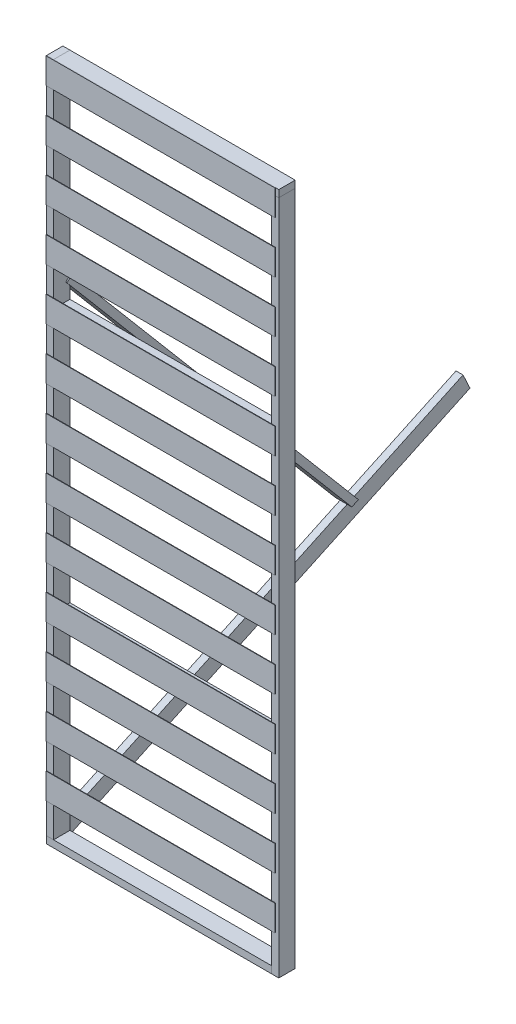
SolidWorks part; units mm, degrees
ref_plane "Front Plane" through (0, 0, 0) normal (0, 0, 1) x (1, 0, 0)
ref_plane "Top Plane" through (0, 0, 0) normal (0, 1, 0) x (1, 0, 0)
ref_plane "Right Plane" through (0, 0, 0) normal (1, 0, 0) x (0, 0, -1)
sketch "Sketch2" plane through (0, 0, 0) normal (0, 0, 1) x (1, 0, 0)
  line L0 (-609.6, 660.4) -> (609.6, 660.4)
  line L1 (-609.6, 1828.8) -> (609.6, 1828.8)
  line L2 (-609.6, 1828.8) -> (-609.6, -1828.8)
  line L3 (-609.6, -1828.8) -> (609.6, -1828.8)
  line L4 (609.6, 1828.8) -> (609.6, -1828.8)
  line L5 (-609.6, 1828.8) -> (609.6, -1828.8) construction
  line L6 (-609.6, -1828.8) -> (609.6, 1828.8) construction
  line L7 (-609.6, -762) -> (609.6, -762)
  point P0 (0, 0)
  dimension "D1" = 3657.6
  dimension "D2" = 1219.2
  dimension "D3" = 1168.4
  dimension "D4" = 1066.8
other "Profiles 2X4(1)"
ref_plane "Plane1" through (-609.6, 1828.8, 0) normal (1, 0, 0) x (0, 1, 0)
sketch "2x4" plane through (-609.6, 1828.8, 0) normal (1, 0, 0) x (0, 1, 0)
  line L1 (-19.05, 44.45) -> (19.05, 44.45)
  line L2 (-19.05, 44.45) -> (-19.05, -44.45)
  line L3 (-19.05, -44.45) -> (19.05, -44.45)
  line L4 (19.05, 44.45) -> (19.05, -44.45)
  line L5 (-19.05, 44.45) -> (19.05, -44.45) construction
  line L6 (-19.05, -44.45) -> (19.05, 44.45) construction
  point P0 (0, 0)
  point P6 (0, 44.45)
  point P7 (-19.05, 0)
  point P8 (19.05, 0)
  point P9 (0, -44.45)
  point P10 (0, 0)
  dimension "D1" = 38.1
  dimension "D2" = 88.9
sketch "Sketch4" plane through (0, 0, 44.45) normal (0, 0, 1) x (1, 0, 0)
  line L0 (609.6, 1828.8) -> (609.6, -1828.8) construction
  line L1 (-628.65, 1847.85) -> (609.6, 1847.85)
  line L2 (-628.65, 1847.85) -> (-628.65, 1708.15)
  line L3 (-628.65, 1708.15) -> (609.6, 1708.15)
  line L4 (609.6, 1847.85) -> (609.6, 1708.15)
  dimension "D1" = 139.7
extrude "Boss-Extrude1" add sketch "Sketch4" along normal blind 2.54 separate body
pattern_linear "LPattern1" count 13 spacing 279.4 along (0, -1, 0) of "Boss-Extrude1"
sketch "Sketch5" plane through (-628.65, 0, 0) normal (-1, 0, 0) x (0, 0, 1)
  line L0 (0, -1828.8) -> (-2209.9409, -798.2876)
  line L1 (0, 1828.8) -> (0, -1828.8) construction
  line L2 (0, -1828.8) -> (0, 1828.8) construction
  line L3 (-36.0861, 783.8333) -> (-1611.4152, -1077.3847)
  dimension "D1" = 65
  dimension "D2" = 2438.4
  dimension "D3" = 2438.4
  dimension "D4" = 1778
  dimension "D5" = 2612.6333
other "Profiles 2X4(3)"
ref_plane "Plane2" through (-628.65, -1828.8, 0) normal (0, 0.4226, -0.9063) x (-1, 0, 0)
sketch "2x41" plane through (-628.65, -1828.8, 0) normal (0, 0.4226, -0.9063) x (-1, 0, 0)
  line L1 (-19.05, 44.45) -> (19.05, 44.45)
  line L2 (-19.05, 44.45) -> (-19.05, -44.45)
  line L3 (-19.05, -44.45) -> (19.05, -44.45)
  line L4 (19.05, 44.45) -> (19.05, -44.45)
  line L5 (-19.05, 44.45) -> (19.05, -44.45) construction
  line L6 (-19.05, -44.45) -> (19.05, 44.45) construction
  point P0 (0, 0)
  point P6 (0, 44.45)
  point P7 (-19.05, 0)
  point P8 (19.05, 0)
  point P9 (0, -44.45)
  point P10 (0, 0)
  dimension "D1" = 38.1
  dimension "D2" = 88.9
